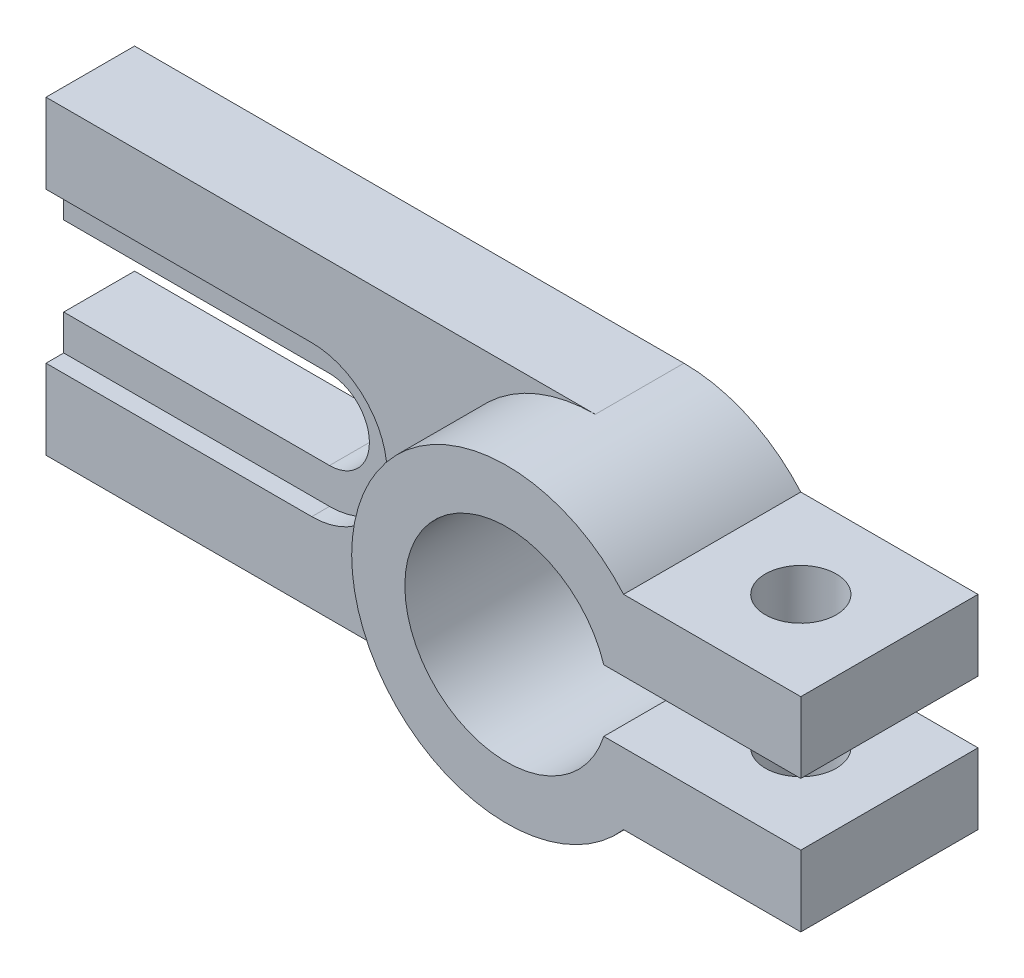
SolidWorks part; units mm, degrees
ref_plane "Plan de face" through (0, 0, 0) normal (0, 0, 1) x (1, 0, 0)
ref_plane "Plan de dessus" through (0, 0, 0) normal (0, 1, 0) x (1, 0, 0)
ref_plane "Plan de droite" through (0, 0, 0) normal (1, 0, 0) x (0, 0, -1)
sketch "Esquisse1" plane through (0, 0, 0) normal (0, 0, 1) x (1, 0, 0)
  line L0 (-62, 17.5) -> (-62, 4.5)
  line L1 (-62, 4.5) -> (-32, 4.5)
  line L2 (-62, 17.5) -> (0, 17.5)
  line L3 (-32, -4.5) -> (-62, -4.5)
  line L4 (-62, -4.5) -> (-62, -17.5)
  line L5 (-62, -17.5) -> (0, -17.5)
  line L6 (13.1909, 11.5) -> (33.1909, 11.5)
  line L7 (33.1909, 11.5) -> (33.1909, 3.5)
  line L8 (33.1909, 3.5) -> (10.9545, 3.5)
  line L9 (10.9545, -3.5) -> (33.1909, -3.5)
  line L10 (33.1909, -3.5) -> (33.1909, -11.5)
  line L11 (33.1909, -11.5) -> (13.1909, -11.5)
  line L12 (-32, 0) -> (-60.9677, 0) construction
  line L13 (10.9545, 3.5) -> (10.9545, -3.5) construction
  line L14 (13.1909, 11.5) -> (13.1909, -11.5) construction
  arc A0 (-32, 4.5) -> (-32, -4.5) centre (-32, 0) cw
  arc A1 (10.9545, 3.5) -> (10.9545, -3.5) centre (0, 0) ccw
  arc A2 (0, 17.5) -> (13.1909, 11.5) centre (0, 0) cw
  arc A3 (13.1909, -11.5) -> (0, -17.5) centre (0, 0) cw
  dimension "D7" = 6
  dimension "D1" = 9
  dimension "D2" = 13
  dimension "D3" = 13
  dimension "D4" = 7
  dimension "D5" = 8
  dimension "D6" = 20
  dimension "D8" = 62
  dimension "D9" = 30
extrude "Boss.-Extru.1" add sketch "Esquisse1" along normal blind 10
sketch "Esquisse2" plane through (0, 0, 10) normal (0, 0, 1) x (1, 0, 0)
  line L0 (13.1909, 11.5) -> (33.1909, 11.5)
  line L1 (33.1909, 11.5) -> (33.1909, 3.5)
  line L2 (33.1909, 3.5) -> (10.9545, 3.5)
  line L3 (10.9545, -3.5) -> (33.1909, -3.5)
  line L4 (33.1909, -3.5) -> (33.1909, -11.5)
  line L5 (33.1909, -11.5) -> (13.1909, -11.5)
  arc A0 (13.1909, 11.5) -> (13.1909, -11.5) centre (0, 0) ccw
  arc A1 (0, -17.5) -> (13.1909, -11.5) centre (0, 0) ccw construction
  arc A2 (10.9545, 3.5) -> (10.9545, -3.5) centre (0, 0) ccw
  arc A3 (10.9545, 3.5) -> (10.9545, -3.5) centre (0, 0) ccw construction
extrude "Boss.-Extru.2" add sketch "Esquisse2" along normal blind 10
sketch "Esquisse3" plane through (0, 0, 10) normal (0, 0, 1) x (1, 0, 0)
  line L0 (-32, 4.5) -> (-62, 4.5)
  line L1 (-62, 4.5) -> (-62, 8.5)
  line L2 (-62, 17.5) -> (-62, 4.5) construction
  line L3 (-62, 8.5) -> (-32, 8.5)
  line L4 (-32, -4.5) -> (-62, -4.5)
  line L5 (-62, -4.5) -> (-62, -8.5)
  line L6 (-62, -4.5) -> (-62, -17.5) construction
  line L7 (-62, -8.5) -> (-32, -8.5)
  arc A0 (-32, 4.5) -> (-32, -4.5) centre (-32, 0) cw
  arc A1 (-32, -8.5) -> (-32, 8.5) centre (-32, 0) ccw
  dimension "D1" = 4
extrude "Enlèv. mat.-Extru.1" cut sketch "Esquisse3" against normal blind 2
sketch "Esquisse4" plane through (0, -11.5, 0) normal (0, -1, 0) x (1, 0, 0)
  line L0 (13.1909, 20) -> (33.1909, 0) construction
  circle A0 centre (23.1909, 10) radius 4
  dimension "D1" = 8
extrude "Enlèv. mat.-Extru.2" cut sketch "Esquisse4" against normal through all
